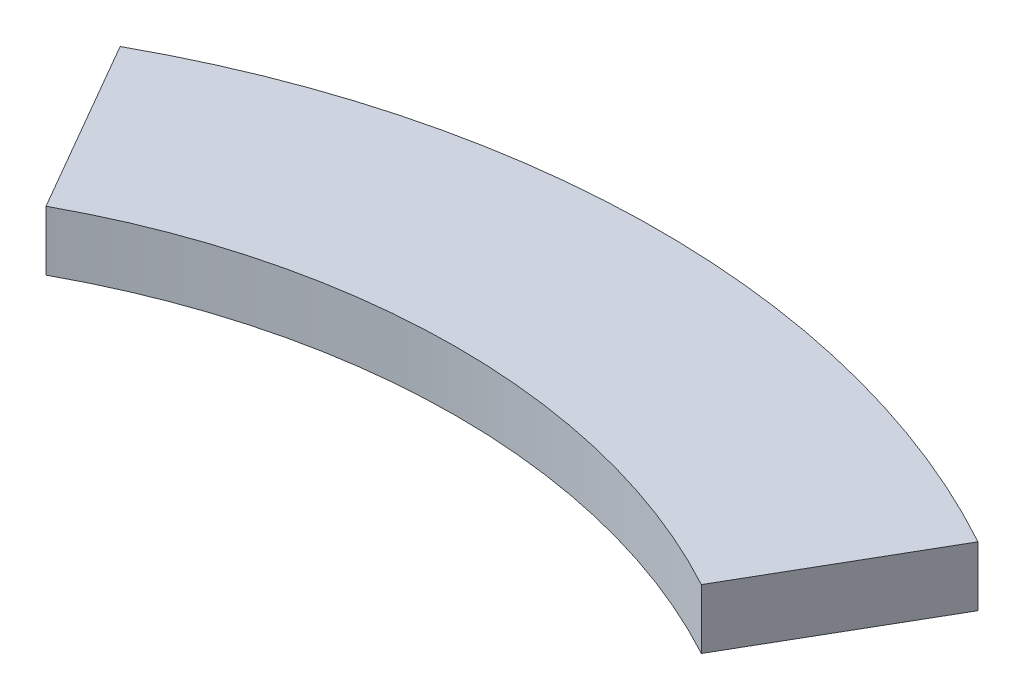
SolidWorks part; units mm, degrees
ref_plane "Front Plane" through (0, 0, 0) normal (0, 0, 1) x (1, 0, 0)
ref_plane "Top Plane" through (0, 0, 0) normal (0, 1, 0) x (1, 0, 0)
ref_plane "Right Plane" through (0, 0, 0) normal (1, 0, 0) x (0, 0, -1)
sketch "Sketch1" plane through (0, 0, 0) normal (0, 1, 0) x (1, 0, 0)
  line L0 (-14, 24.2487) -> (-19, 32.909) construction
  line L1 (14, 24.2487) -> (19, 32.909) construction
  line L2 (0, 0) -> (4, 0) construction
  line L3 (-17.9717, 32.6279) -> (-13.7293, 25.2798)
  line L4 (17.9717, 32.6279) -> (13.7293, 25.2798)
  line L5 (-16.5, 28.5788) -> (-15.8505, 28.9538) construction
  line L6 (15.8505, 28.9538) -> (16.5, 28.5788) construction
  circle A0 centre (0, 0) radius 28 construction
  circle A1 centre (0, 0) radius 38 construction
  arc A2 (-17.9717, 32.6279) -> (17.9717, 32.6279) centre (0, 0) cw
  arc A3 (-13.7293, 25.2798) -> (13.7293, 25.2798) centre (0, 0) cw
  point P19 (16.5, 28.5788)
  dimension "D1" = 28
  dimension "D2" = 38
  dimension "D4" = 0.75
  dimension "D6" = 60
  dimension "D3" = 60
  dimension "D5" = 0.75
extrude "Boss-Extrude1" add sketch "Sketch1" along normal blind 2.5
sketch "Sketch2" plane through (0, 0, 0) normal (0, -1, 0) x (1, 0, 0)
  line L0 (0, -37.25) -> (0, -28.7673) construction
  arc A0 (-17.9717, -32.6279) -> (17.9717, -32.6279) centre (0, 0) ccw construction
  arc A1 (-13.7293, -25.2798) -> (13.7293, -25.2798) centre (0, 0) ccw construction
  circle A2 centre (0, -33.0087) radius 1.625
  dimension "D1" = 3.25
extrude "Cut-Extrude1" cut sketch "Sketch2" against normal blind 2
